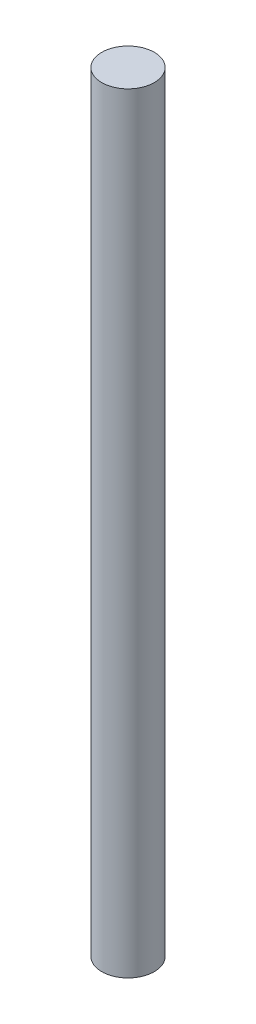
SolidWorks part; units mm, degrees
ref_plane "Front Plane" through (0, 0, 0) normal (0, 0, 1) x (1, 0, 0)
ref_plane "Top Plane" through (0, 0, 0) normal (0, 1, 0) x (1, 0, 0)
ref_plane "Right Plane" through (0, 0, 0) normal (1, 0, 0) x (0, 0, -1)
sketch "Sketch1" plane through (0, 0, 0) normal (0, 1, 0) x (1, 0, 0)
  circle A0 centre (0, 0) radius 1.3
  dimension "D1" = 2.6
extrude "Boss-Extrude1" add sketch "Sketch1" along normal blind 38.1
